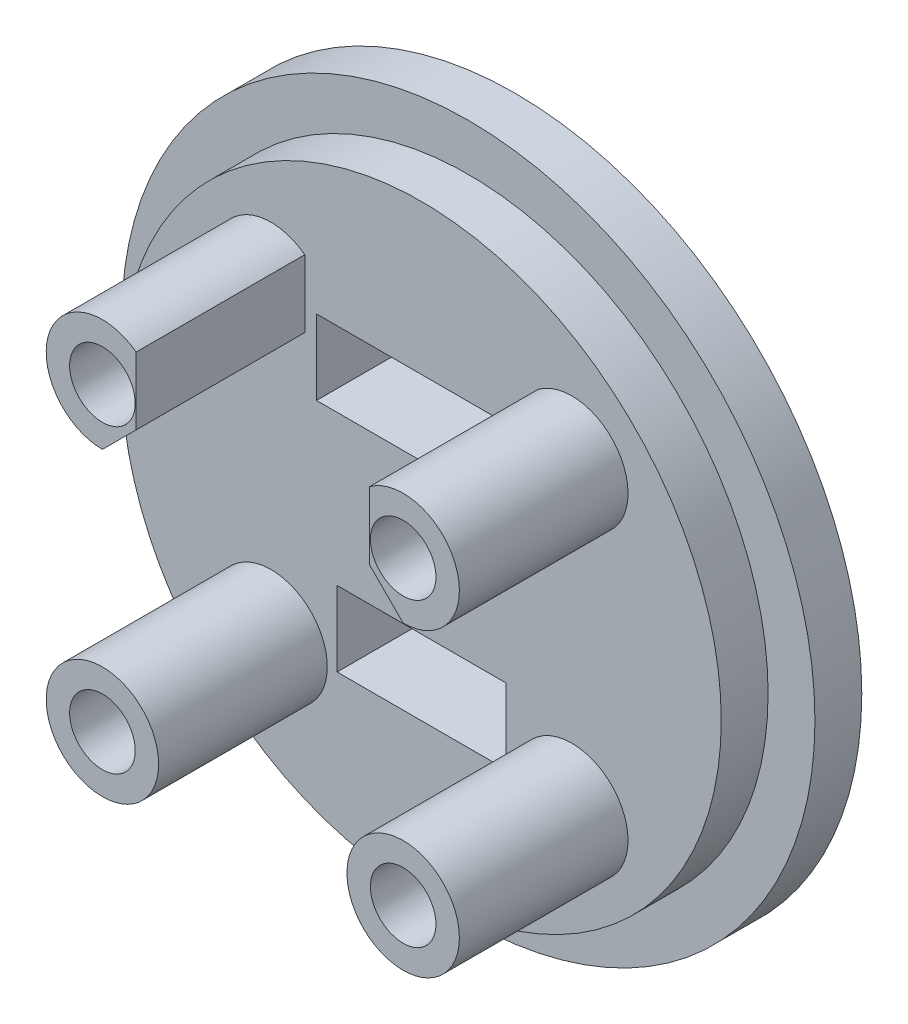
SolidWorks part; units mm, degrees
ref_plane "Alzado" through (0, 0, 0) normal (0, 0, 1) x (1, 0, 0)
ref_plane "Planta" through (0, 0, 0) normal (0, 1, 0) x (1, 0, 0)
ref_plane "Vista lateral" through (0, 0, 0) normal (1, 0, 0) x (0, 0, -1)
sketch "Croquis1" plane through (0, 0, 0) normal (0, 0, 1) x (1, 0, 0)
  circle A0 centre (0, 0) radius 16
  dimension "D1" = 32
extrude "Saliente-Extruir1" add sketch "Croquis1" along normal blind 5
sketch "Croquis2" plane through (0, 0, 5) normal (0, 0, 1) x (1, 0, 0)
  line L1 (-8.025, 8.025) -> (8.025, 8.025) construction
  line L2 (-8.025, 8.025) -> (-8.025, -8.025) construction
  line L3 (-8.025, -8.025) -> (8.025, -8.025) construction
  line L4 (8.025, 8.025) -> (8.025, -8.025) construction
  line L5 (-8.025, 8.025) -> (8.025, -8.025) construction
  line L6 (-8.025, -8.025) -> (8.025, 8.025) construction
  circle A0 centre (-8.025, 8.025) radius 1.75
  circle A1 centre (8.025, 8.025) radius 1.75
  circle A2 centre (8.025, -8.025) radius 1.75
  circle A3 centre (-8.025, -8.025) radius 1.75
  point P0 (0, 0)
  dimension "D3" = 3.5
  dimension "D4" = 3.5
  dimension "D5" = 3.5
  dimension "D6" = 3.5
  dimension "D1" = 16.05
  dimension "D2" = 16.05
extrude "Cortar-Extruir1" cut sketch "Croquis2" against normal through all
sketch "Croquis3" plane through (0, 0, 0) normal (0, 0, -1) x (-1, 0, 0)
  line L0 (0, 0) -> (0, 10.3347) construction
  line L1 (-4.5609, 8.025) -> (-6.2929, 11.025)
  line L2 (-6.2929, 11.025) -> (-9.7571, 11.025)
  line L3 (-9.7571, 11.025) -> (-11.4891, 8.025)
  line L4 (-11.4891, 8.025) -> (-9.7571, 5.025)
  line L5 (-9.7571, 5.025) -> (-6.2929, 5.025)
  line L6 (-6.2929, 5.025) -> (-4.5609, 8.025)
  line L7 (6.2929, 5.025) -> (4.5609, 8.025)
  line L8 (9.7571, 5.025) -> (6.2929, 5.025)
  line L9 (11.4891, 8.025) -> (9.7571, 5.025)
  line L10 (9.7571, 11.025) -> (11.4891, 8.025)
  line L11 (6.2929, 11.025) -> (9.7571, 11.025)
  line L12 (4.5609, 8.025) -> (6.2929, 11.025)
  line L13 (0, 0) -> (10.6019, 0) construction
  line L14 (9.7571, -5.025) -> (6.2929, -5.025)
  line L15 (11.4891, -8.025) -> (9.7571, -5.025)
  line L16 (9.7571, -11.025) -> (11.4891, -8.025)
  line L17 (6.2929, -11.025) -> (9.7571, -11.025)
  line L18 (4.5609, -8.025) -> (6.2929, -11.025)
  line L19 (6.2929, -5.025) -> (4.5609, -8.025)
  line L20 (-6.2929, -5.025) -> (-4.5609, -8.025)
  line L21 (-9.7571, -5.025) -> (-6.2929, -5.025)
  line L22 (-11.4891, -8.025) -> (-9.7571, -5.025)
  line L23 (-9.7571, -11.025) -> (-11.4891, -8.025)
  line L24 (-6.2929, -11.025) -> (-9.7571, -11.025)
  line L25 (-4.5609, -8.025) -> (-6.2929, -11.025)
  circle A0 centre (-8.025, 8.025) radius 3 construction
  dimension "D1" = 6
  dimension "D2" = 30
extrude "Cortar-Extruir2" cut sketch "Croquis3" against normal blind 3
sketch "Croquis4" plane through (0, 0, 5) normal (0, 0, 1) x (1, 0, 0)
  circle A0 centre (-8.025, 8.025) radius 3
  circle A1 centre (8.025, 8.025) radius 3
  circle A2 centre (-8.025, -8.025) radius 3
  circle A3 centre (8.025, -8.025) radius 3
  circle A4 centre (-8.025, 8.025) radius 1.75
  circle A5 centre (8.025, 8.025) radius 1.75
  circle A6 centre (8.025, -8.025) radius 1.75
  circle A7 centre (-8.025, -8.025) radius 1.75
  dimension "D1" = 6
  dimension "D2" = 6
  dimension "D3" = 6
  dimension "D4" = 6
extrude "Saliente-Extruir2" add sketch "Croquis4" along normal blind 9
sketch "Croquis5" plane through (0, 0, 14) normal (0, 0, 1) x (1, 0, 0)
  line L0 (-5.025, 8.025) -> (-8.025, 5.025)
  line L1 (0, 0) -> (0, 9.1307) construction
  line L2 (5.025, 8.025) -> (8.025, 5.025)
  circle A0 centre (-8.025, 8.025) radius 3 construction
  circle A1 centre (-8.025, 8.025) radius 3 construction
  arc A2 (-8.025, 5.025) -> (-5.025, 8.025) centre (-8.025, 8.025) ccw
  arc A3 (8.025, 5.025) -> (5.025, 8.025) centre (8.025, 8.025) cw
extrude "Cortar-Extruir3" cut sketch "Croquis5" against normal up to surface (9 mm away) up to face at (-5.025, -8.025, 5)
sketch "Croquis6" plane through (0, 0, 14) normal (0, 0, 1) x (1, 0, 0)
  line L3 (-6.2243, 6.8257) -> (-5.025, 8.025)
  line L4 (0, 0) -> (0, 8.871) construction
  line L8 (-6.2243, 10.4245) -> (-6.2243, 6.8257)
  line L9 (6.2243, 10.4245) -> (6.2243, 6.8257)
  line L10 (6.2243, 6.8257) -> (5.025, 8.025)
  arc A2 (-5.025, 8.025) -> (-6.2243, 10.4245) centre (-8.025, 8.025) ccw
  arc A4 (5.025, 8.025) -> (6.2243, 10.4245) centre (8.025, 8.025) cw
extrude "Cortar-Extruir7" cut sketch "Croquis6" against normal up to surface (9 mm away) up to face at (-5.025, -8.025, 5)
sketch "Croquis7" plane through (0, 0, 5) normal (0, 0, 1) x (1, 0, 0)
  line L0 (-5.6, 8) -> (5.6, 8)
  line L1 (-5.6, 8) -> (-5.6, 4)
  line L2 (-5.6, 4) -> (5.6, 4)
  line L3 (5.6, 4) -> (5.6, 8)
  line L4 (0, 0) -> (0, -6) construction
  line L6 (-4.5, -4) -> (4.5, -4)
  line L7 (-4.5, -4) -> (-4.5, -8)
  line L8 (-4.5, -8) -> (4.5, -8)
  line L9 (4.5, -4) -> (4.5, -8)
  line L10 (-4.5, -4) -> (4.5, -8) construction
  line L11 (-4.5, -8) -> (4.5, -4) construction
  circle A2 centre (0, 0) radius 16 construction
  dimension "D1" = 8
  dimension "D2" = 4
  dimension "D3" = 11.2
  dimension "D4" = 5.6
  dimension "D5" = 8
  dimension "D6" = 4
  dimension "D7" = 9
extrude "Cortar-Extruir8" cut sketch "Croquis7" against normal through all
sketch "Croquis8" plane through (0, 0, 0) normal (0, 0, -1) x (-1, 0, 0)
  circle A0 centre (0, 0) radius 18.5
  circle A1 centre (0, 0) radius 16
  dimension "D1" = 37
extrude "Saliente-Extruir3" add sketch "Croquis8" against normal blind 2.5
